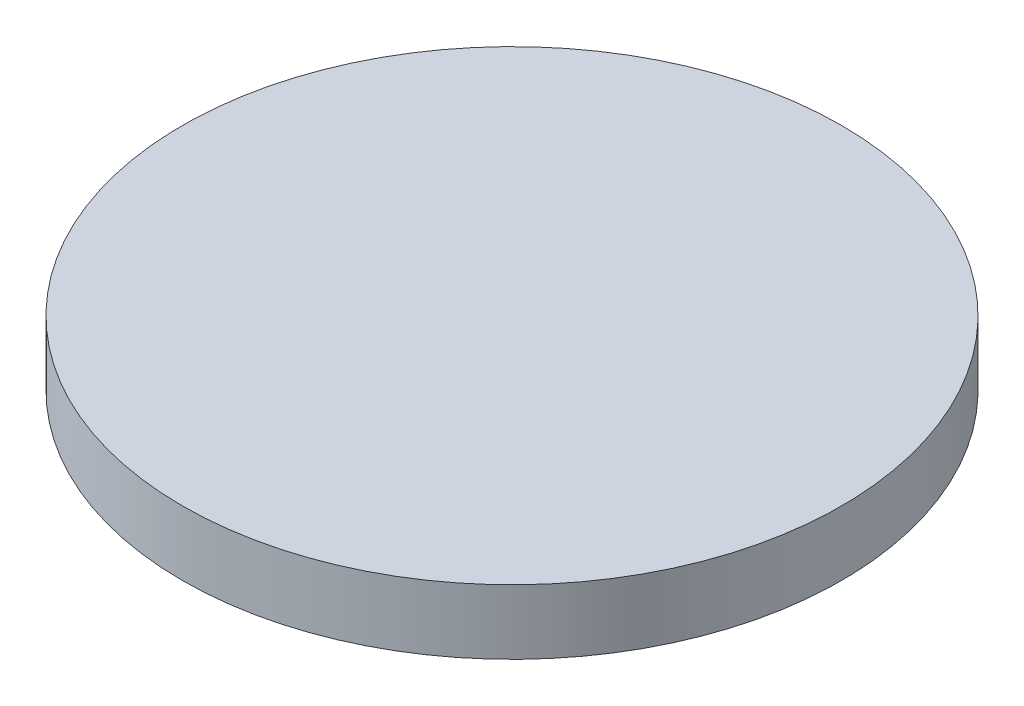
SolidWorks part; units mm, degrees
ref_plane "Front Plane" through (0, 0, 0) normal (0, 0, 1) x (1, 0, 0)
ref_plane "Top Plane" through (0, 0, 0) normal (0, 1, 0) x (1, 0, 0)
ref_plane "Right Plane" through (0, 0, 0) normal (1, 0, 0) x (0, 0, -1)
sketch "Sketch2" plane through (0, 0, 0) normal (0, 1, 0) x (1, 0, 0)
  circle A0 centre (0, 0) radius 25.5
  dimension "D1" = 51
extrude "Boss-Extrude1" add sketch "Sketch2" along normal blind 5
